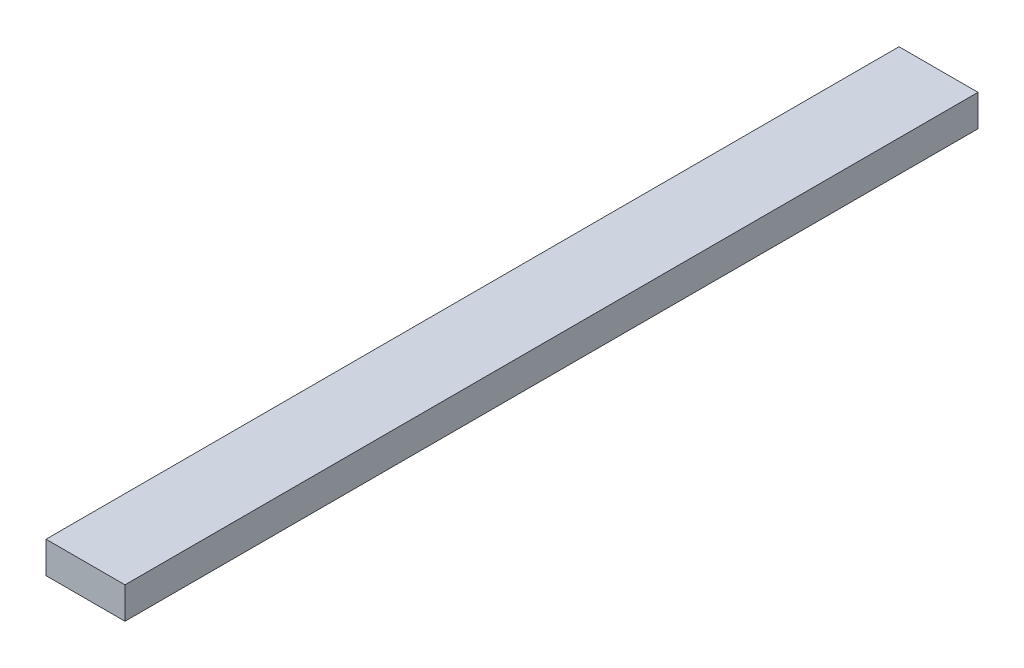
SolidWorks part; units mm, degrees
ref_plane "Front Plane" through (0, 0, 0) normal (0, 0, 1) x (1, 0, 0)
ref_plane "Top Plane" through (0, 0, 0) normal (0, 1, 0) x (1, 0, 0)
ref_plane "Right Plane" through (0, 0, 0) normal (1, 0, 0) x (0, 0, -1)
sketch "Sketch1" plane through (0, 0, 0) normal (0, 1, 0) x (1, 0, 0)
  line L1 (0, 0) -> (25, 0)
  line L2 (0, 0) -> (0, 270)
  line L3 (0, 270) -> (25, 270)
  line L4 (25, 0) -> (25, 270)
  dimension "D1" = 270
  dimension "D2" = 25
extrude "Boss-Extrude1" add sketch "Sketch1" along normal blind 10
